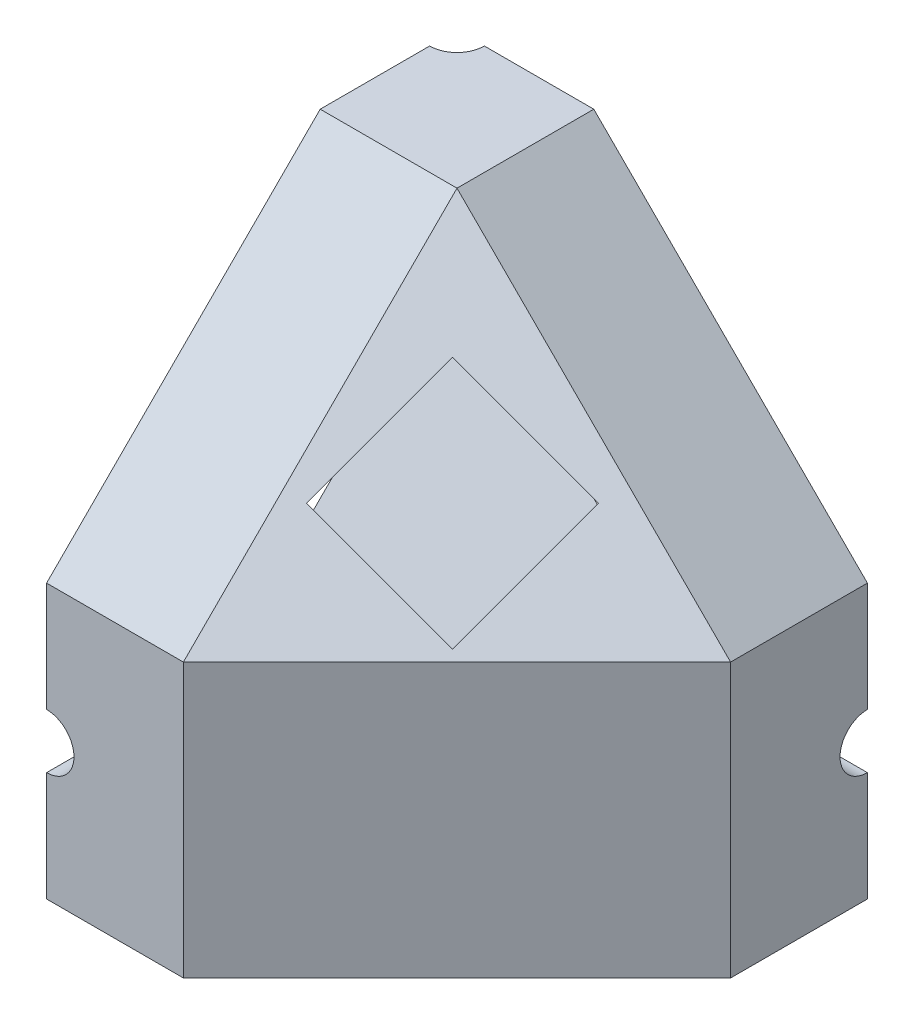
SolidWorks part; units mm, degrees
ref_plane "Front Plane" through (0, 0, 0) normal (0, 0, 1) x (1, 0, 0)
ref_plane "Top Plane" through (0, 0, 0) normal (0, 1, 0) x (1, 0, 0)
ref_plane "Right Plane" through (0, 0, 0) normal (1, 0, 0) x (0, 0, -1)
sketch "Sketch1" plane through (0, 0, 0) normal (0, 0, 1) x (1, 0, 0)
  line L1 (0, 0) -> (30, 0)
  line L2 (0, 0) -> (0, 30)
  line L3 (0, 30) -> (30, 30)
  line L4 (30, 0) -> (30, 30)
  dimension "D1" = 30
  dimension "D2" = 30
extrude "Boss-Extrude1" add sketch "Sketch1" against normal blind 30
sketch "Sketch2" plane through (0, 0, 0) normal (0, 0, 1) x (1, 0, 0)
  line L0 (15, 30) -> (30, 15)
  line L1 (30, 30) -> (0, 30) construction
  line L2 (30, 0) -> (30, 30) construction
  line L3 (30, 15) -> (45, 15)
  line L4 (45, 15) -> (45, 45.6191)
  line L5 (45, 45.6191) -> (15, 40.3683)
  line L6 (15, 40.3683) -> (15, 30)
  dimension "D1" = 15
  dimension "D2" = 15
  dimension "D3" = 15
extrude "Cut-Extrude1" cut sketch "Sketch2" against normal blind 30
sketch "Sketch3" plane through (0, 0, 0) normal (-1, 0, 0) x (0, 0, 1)
  line L0 (0, 15) -> (-15, 30)
  line L1 (0, 30) -> (0, 0) construction
  line L2 (-30, 30) -> (0, 30) construction
  line L3 (-15, 30) -> (-15, 36.1773)
  line L4 (-15, 36.1773) -> (9.5396, 36.1773)
  line L5 (9.5396, 36.1773) -> (9.5396, 15)
  line L6 (9.5396, 15) -> (0, 15)
  dimension "D1" = 15
extrude "Cut-Extrude2" cut sketch "Sketch3" against normal blind 30
sketch "Sketch4" plane through (0, 0, 0) normal (0, -1, 0) x (1, 0, 0)
  line L0 (15, 0) -> (30, -15)
  line L1 (0, 0) -> (30, 0) construction
  line L2 (30, -30) -> (30, 0) construction
  line L3 (30, -15) -> (40.2278, -15)
  line L4 (40.2278, -15) -> (40.2278, 9.3171)
  line L5 (40.2278, 9.3171) -> (15, 8.9664)
  line L6 (15, 8.9664) -> (15, 0)
extrude "Cut-Extrude3" cut sketch "Sketch4" against normal blind 30
sketch3d "3DSketch1"
  line L1 (33.9969, 3.57, -7.567) -> (10, 10, 10)
  line L2 (33.9969, 3.57, -7.567) -> (45.4692, 15.0424, 3.9054)
  line L3 (45.4692, 15.0424, 3.9054) -> (21.4723, 21.4723, 21.4723)
  line L4 (10, 10, 10) -> (21.4723, 21.4723, 21.4723)
  point P7 (32.9904, 3.8397, -6.8301)
  point P8 (32.9904, 3.8397, -6.8301)
  point P9 (32.9904, 3.8397, -6.8301)
  point P10 (32.9904, 3.8397, -6.8301)
  dimension "D1" = 0
extrude "Cut-Extrude4" cut sketch "3DSketch1" along a picked direction on the side of the normal blind 30
sketch "Sketch5" plane through (10, 10, 10) normal (0.5774, 0.5774, 0.5774) x (0.4082, 0.4082, -0.8165)
  line L0 (19.4571, 2.9469) -> (27.1845, 5.0174)
  line L1 (27.1845, 5.0174) -> (29.255, -2.71)
  line L2 (29.255, -2.71) -> (21.5276, -4.7806)
  line L3 (21.5276, -4.7806) -> (19.4571, 2.9469)
  line L4 (12.2474, 0) -> (30.6186, -10.6066) construction
  dimension "D1" = 8
  dimension "D2" = 8
  dimension "D3" = 0.5
  dimension "D4" = 45
extrude "Cut-Extrude5" cut sketch "Sketch5" against normal blind 15
sketch "Sketch6" plane through (0, 30, 0) normal (0, 1, 0) x (1, 0, 0)
  line L0 (15, 30) -> (0, 30) construction
  line L1 (0, 30) -> (0, 15) construction
  circle A0 centre (7.5, 22.5) radius 1.5
  point P4 (7.5, 30)
  dimension "D1" = 3
  dimension "D2" = 7.5
  dimension "D3" = 7.5
sketch "Sketch8" plane through (0, 0, 0) normal (0, 0, 1) x (1, 0, 0)
  line L0 (0, 15) -> (0, 0) construction
  line L1 (0, 0) -> (15, 0) construction
  circle A0 centre (7.5, 7.5) radius 1.5
  dimension "D1" = 3
  dimension "D2" = 7.5
  dimension "D3" = 7.5
sketch "Sketch10" plane through (30, 0, 0) normal (1, 0, 0) x (0, 0, -1)
  line L0 (30, 0) -> (30, 15) construction
  line L1 (30, 0) -> (15, 0) construction
  circle A0 centre (22.5, 7.5) radius 1.5
  dimension "D1" = 3
  dimension "D2" = 7.5
  dimension "D3" = 7.5
extrude "Cut-Extrude6" cut sketch "Sketch6" against normal blind 20 contours A0
extrude "Cut-Extrude8" cut sketch "Sketch8" against normal blind 20
extrude "Cut-Extrude10" cut sketch "Sketch10" against normal blind 20
sketch "Sketch14" plane through (0, 30, 0) normal (0, 1, 0) x (1, 0, 0)
  line L3 (0, 31.6) -> (32.5211, 31.6)
  line L9 (6, 22.5) -> (0, 22.5)
  line L10 (0, 30) -> (0, 15) construction
  line L11 (0, 22.5) -> (0, 31.6)
  line L12 (6, 22.5) -> (32.5211, 22.5)
  line L13 (32.5211, 22.5) -> (32.5211, 31.6)
  circle A1 centre (7.5, 22.5) radius 1.5 construction
extrude "Cut-Extrude12" cut sketch "Sketch14" against normal through all
sketch "Sketch16" plane through (0, 0, 0) normal (-1, 0, 0) x (0, 0, 1)
  line L10 (0, 0) -> (-28.6645, 0)
  line L11 (0, 0) -> (0, 34.476)
  line L12 (0, 34.476) -> (-28.6645, 34.476)
  line L13 (-28.6645, 0) -> (-28.6645, 34.476)
extrude "Cut-Extrude13" cut sketch "Sketch16" against normal blind 7.5
sketch "Sketch18" plane through (7.5, 0, 0) normal (-1, 0, 0) x (0, 0, 1)
  line L0 (0, 0) -> (0, 6) construction
  line L1 (-22.5, 0) -> (0, 0) construction
  line L2 (-21, 30) -> (-15, 30) construction
  line L3 (-22.5, 30) -> (-22.5, 10) construction
  circle A0 centre (-17.5, 24) radius 1
  circle A1 centre (-6, 3) radius 1
  dimension "D1" = 6
  dimension "D2" = 3
  dimension "D3" = 6
  dimension "D4" = 5
extrude "Cut-Extrude14" cut sketch "Sketch18" against normal blind 10
sketch "Sketch19" plane through (0, 0, -22.5) normal (0, 0, -1) x (-1, 0, 0)
  line L0 (-30, 15) -> (-30, 9) construction
  line L1 (-7.5, 0) -> (-30, 0) construction
  line L3 (-30, 6) -> (-30, 0) construction
  circle A0 centre (-25, 14) radius 1
  circle A1 centre (-18, 3) radius 1
  dimension "D1" = 5
  dimension "D2" = 14
  dimension "D3" = 3
  dimension "D4" = 12
extrude "Cut-Extrude15" cut sketch "Sketch19" against normal blind 10
